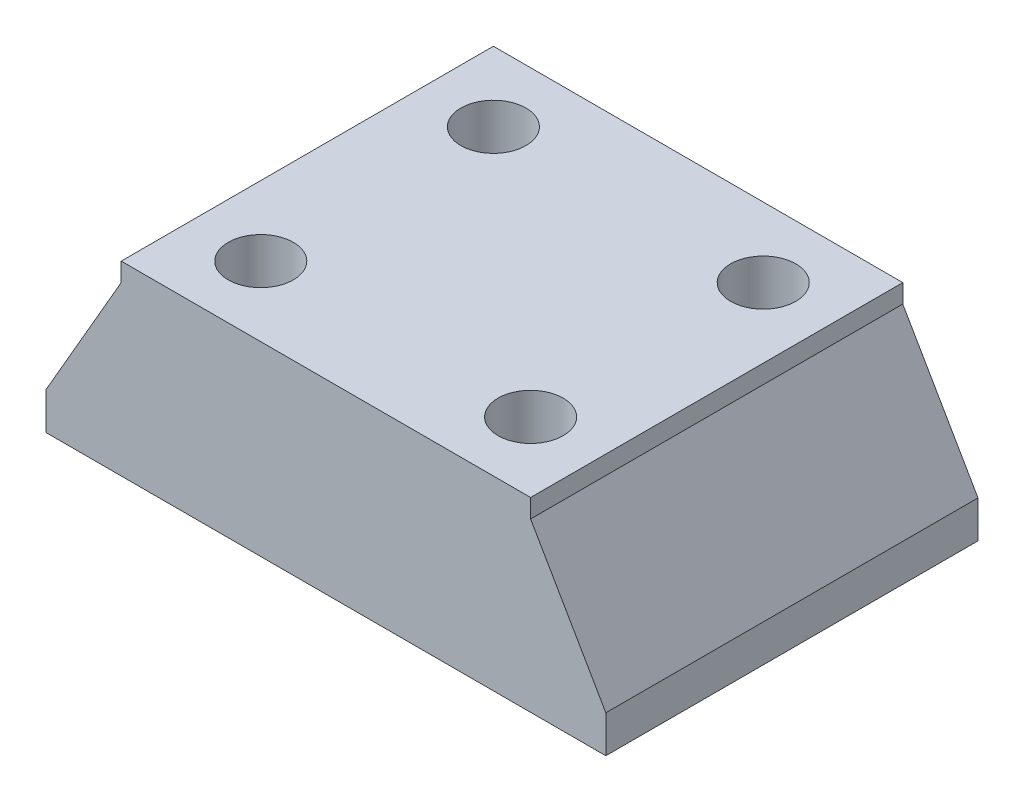
SolidWorks part; units mm, degrees
ref_plane "Piano frontale" through (0, 0, 0) normal (0, 0, 1) x (1, 0, 0)
ref_plane "Piano superiore" through (0, 0, 0) normal (0, 1, 0) x (1, 0, 0)
ref_plane "Piano destro" through (0, 0, 0) normal (1, 0, 0) x (0, 0, -1)
sketch "Schizzo1" plane through (0, 0, 0) normal (0, 0, 1) x (1, 0, 0)
  line L0 (0, 10) -> (0, 0) construction
  line L1 (11, 9) -> (11, 10)
  line L2 (-11, 10) -> (11, 10)
  line L3 (11, 9) -> (15.0415, 2)
  line L4 (15.0415, 2) -> (15.0415, 0)
  line L5 (-15.0415, 0) -> (15.0415, 0)
  line L6 (-15.0415, 2) -> (-15.0415, 0)
  line L7 (-11, 9) -> (-15.0415, 2)
  line L8 (-11, 9) -> (-11, 10)
  point P16 (0, 9.6)
  dimension "D1" = 150
  dimension "D2" = 2
  dimension "D3" = 1
  dimension "D4" = 11
  dimension "D5" = 10
extrude "Estrusione-Estrusione1" add sketch "Schizzo1" along normal mid plane 20
sketch "Schizzo2" plane through (0, 10, 0) normal (0, 1, 0) x (1, 0, 0)
  line L0 (11, -10) -> (11, 10) construction
  line L1 (-7.25, -6.25) -> (7.25, -6.25) construction
  line L2 (-7.25, -6.25) -> (-7.25, 6.25) construction
  line L3 (-7.25, 6.25) -> (7.25, 6.25) construction
  line L4 (7.25, -6.25) -> (7.25, 6.25) construction
  line L5 (-7.25, -6.25) -> (7.25, 6.25) construction
  line L6 (-7.25, 6.25) -> (7.25, -6.25) construction
  line L8 (11, 10) -> (-11, 10) construction
  circle A0 centre (7.25, 6.25) radius 1.75
  circle A1 centre (-7.25, 6.25) radius 1.75
  circle A2 centre (-7.25, -6.25) radius 1.75
  circle A3 centre (7.25, -6.25) radius 1.75
  point P0 (0, 0)
  dimension "D3" = 3.5
  dimension "D1" = 3.75
  dimension "D2" = 3.75
extrude "Taglio-Estrusione1" cut sketch "Schizzo2" against normal through all
